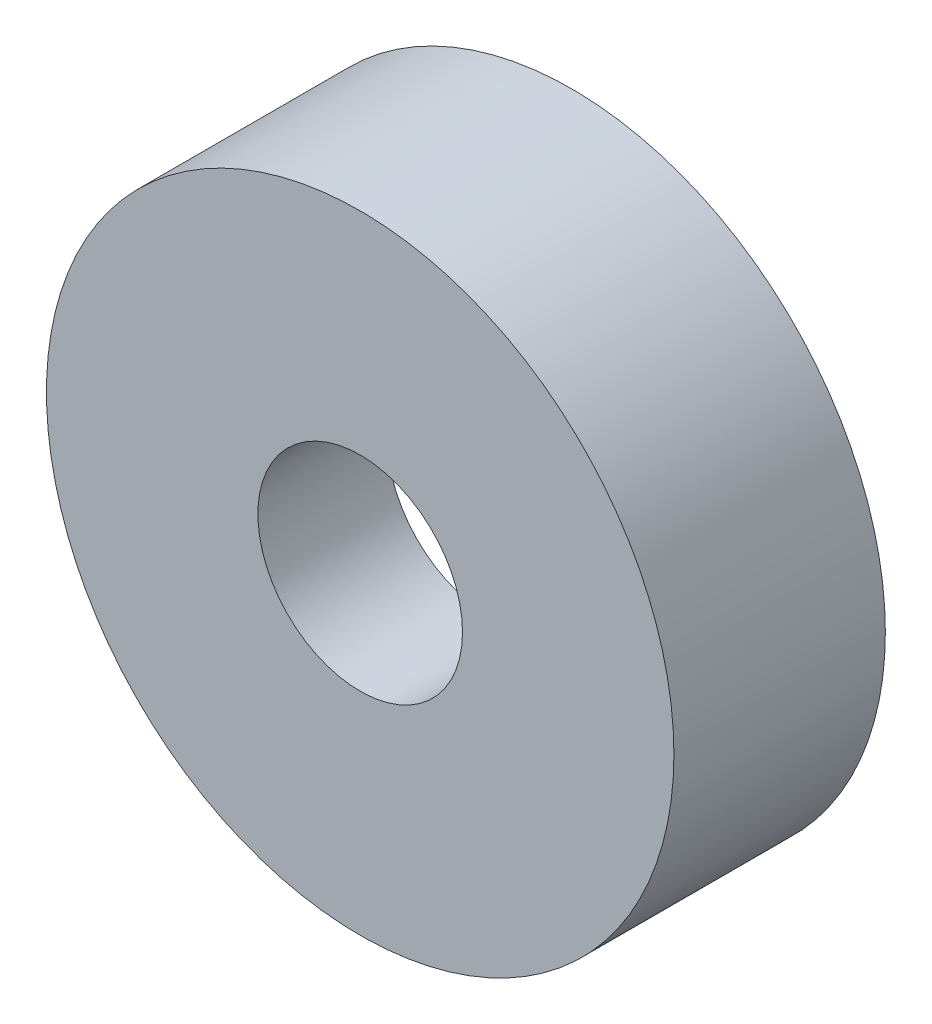
SolidWorks part; units mm, degrees
ref_plane "前视基准面" through (0, 0, 0) normal (0, 0, 1) x (1, 0, 0)
ref_plane "上视基准面" through (0, 0, 0) normal (0, 1, 0) x (1, 0, 0)
ref_plane "右视基准面" through (0, 0, 0) normal (1, 0, 0) x (0, 0, -1)
sketch "草图1" plane through (0, 0, 0) normal (0, 0, 1) x (1, 0, 0)
  circle A0 centre (0, 0) radius 21
  circle A1 centre (0, 0) radius 23
  dimension "D1" = 42
  dimension "D2" = 46
extrude "凸台-拉伸1" add sketch "草图1" along normal blind 6
sketch "草图2" plane through (0, 0, 6) normal (0, 0, 1) x (1, 0, 0)
  circle A0 centre (0, 0) radius 7.5
  circle A1 centre (0, 0) radius 23
  dimension "D1" = 15
extrude "凸台-拉伸2" add sketch "草图2" along normal blind 9.5
